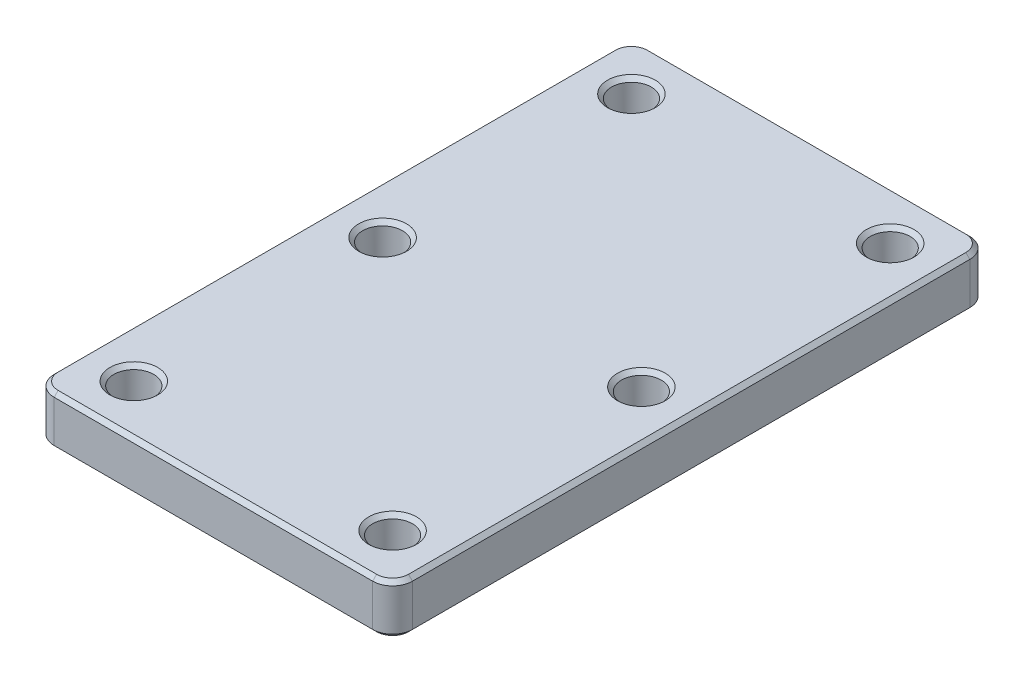
SolidWorks part; units mm, degrees
ref_plane "Front Plane" through (0, 0, 0) normal (0, 0, 1) x (1, 0, 0)
ref_plane "Top Plane" through (0, 0, 0) normal (0, 1, 0) x (1, 0, 0)
ref_plane "Right Plane" through (0, 0, 0) normal (1, 0, 0) x (0, 0, -1)
sketch "Sketch1" plane through (0, 0, 0) normal (0, 1, 0) x (1, 0, 0)
  line L1 (0, 0) -> (180, 0)
  line L2 (0, 0) -> (0, 300)
  line L3 (0, 300) -> (180, 300)
  line L4 (180, 0) -> (180, 300)
  dimension "D1" = 180
  dimension "D2" = 300
extrude "Boss-Extrude1" add sketch "Sketch1" along normal blind 25
sketch "Sketch2" plane through (0, 25, 0) normal (0, 1, 0) x (1, 0, 0)
  line L0 (90, 0) -> (90, 300) construction
  line L1 (0, 0) -> (180, 0) construction
  line L2 (180, 300) -> (0, 300) construction
  line L3 (25, 0) -> (155, 0)
  line L4 (15, 150) -> (190.8774, 150) construction
  line L5 (180, 275) -> (180, 25)
  line L6 (180, 0) -> (180, 300) construction
  line L7 (165, 25) -> (145, 25) construction
  line L8 (155, 15) -> (155, 35) construction
  line L9 (25, 0) -> (25, 35) construction
  line L10 (0, 25) -> (35, 25) construction
  line L11 (155, 300) -> (155, 265) construction
  line L12 (180, 275) -> (145, 275) construction
  line L13 (0, 275) -> (35, 275) construction
  line L14 (25, 300) -> (25, 265) construction
  line L15 (155, 160) -> (155, 140) construction
  line L16 (165, 275) -> (145, 275) construction
  line L17 (155, 285) -> (155, 265) construction
  line L18 (25, 300) -> (25, 265) construction
  line L19 (0, 275) -> (35, 275) construction
  circle A0 centre (155, 25) radius 10
  circle A1 centre (25, 25) radius 10
  circle A2 centre (155, 150) radius 10
  circle A3 centre (25, 150) radius 10
  circle A4 centre (155, 275) radius 10
  circle A5 centre (25, 275) radius 10
  point P15 (180, 150)
  point P37 (90, 150)
  dimension "D3" = 20
  dimension "D4" = 20
  dimension "D1" = 65
  dimension "D2" = 125
extrude "Cut-Extrude1" cut sketch "Sketch2" against normal through all contours A1 | A0 | A2 | A4 | A3 | A5
fillet "Fillet1" radius 10 4 edges at (180, 12.5, -300) (0, 12.5, -300) (0, 12.5, 0) (180, 12.5, 0)
chamfer "Chamfer2" distance 2 angle 45 16 edges at (90, 0, 0) (177.0711, 0, -2.9289) (2.9289, 0, -2.9289) (180, 0, -150) (0, 0, -150) (177.0711, 0, -297.0711) (2.9289, 0, -297.0711) (90, 0, -300) (90, 25, 0) (177.0711, 25, -2.9289) (2.9289, 25, -2.9289) (180, 25, -150) (0, 25, -150) (177.0711, 25, -297.0711) (2.9289, 25, -297.0711) (90, 25, -300)
chamfer "Chamfer3" distance 2 angle 45 6 edges at (25, 25, -15) (25, 25, -140) (25, 25, -265) (155, 25, -265) (155, 25, -140) (155, 25, -15)
